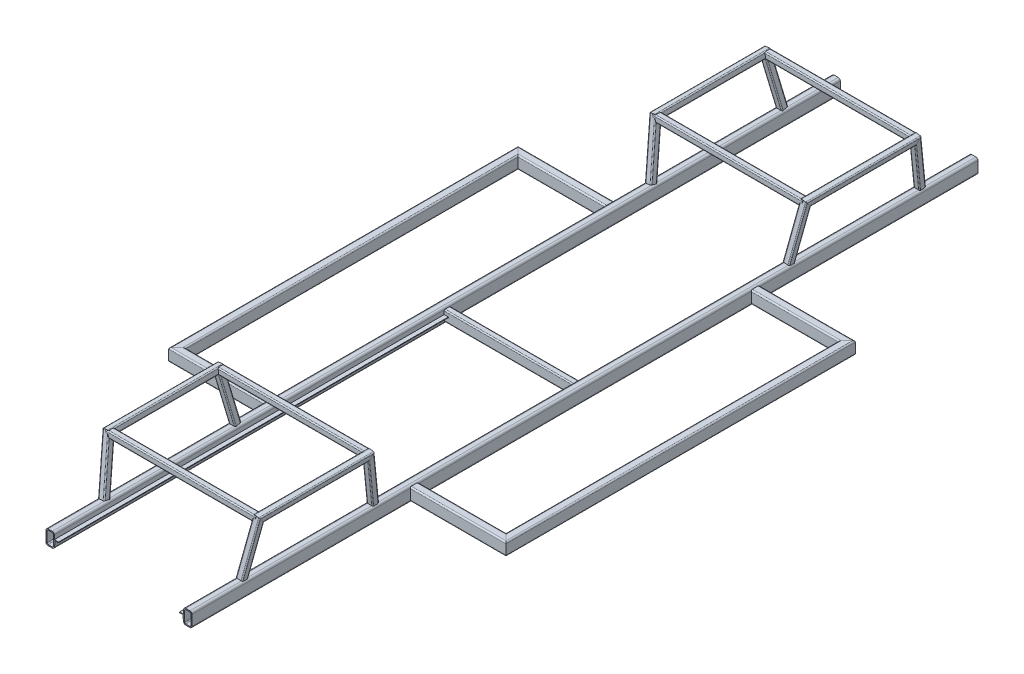
SolidWorks part; units mm, degrees
ref_plane "Płaszczyzna przednia" through (0, 0, 0) normal (0, 0, 1) x (1, 0, 0)
ref_plane "Płaszczyzna górna" through (0, 0, 0) normal (0, 1, 0) x (1, 0, 0)
ref_plane "Płaszczyzna prawa" through (0, 0, 0) normal (1, 0, 0) x (0, 0, -1)
sketch "Szkic1" plane through (0, 0, 0) normal (0, 1, 0) x (1, 0, 0)
  line L0 (-331, 3195) -> (-331, -585)
  line L1 (331, 3195) -> (331, -585)
  line L2 (0, 0) -> (0, -50000) construction
  line L3 (0, 0) -> (-50000, 0) construction
  line L4 (-331, 3195) -> (-50331, 3195) construction
  line L5 (-331, 1305) -> (331, 1305) construction
  line L6 (-331, 85) -> (331, 85) construction
  line L7 (-331, 2525) -> (331, 2525) construction
  line L8 (-331, 485) -> (-791, 485) construction
  line L9 (-791, 485) -> (-791, 2125) construction
  line L10 (-791, 2125) -> (-331, 2125) construction
  line L11 (331, 2125) -> (791, 2125) construction
  line L12 (791, 2125) -> (791, 485) construction
  line L13 (791, 485) -> (331, 485) construction
  dimension "D1" = 331
  dimension "D2" = 331
  dimension "D3" = 3780
  dimension "D4" = 3195
  dimension "D5" = 1220
  dimension "D6" = 1220
  dimension "D7" = 460
  dimension "D8" = 460
  dimension "D9" = 820
  dimension "D10" = 820
  dimension "D11" = 820
other "Rura prostokątna 70 X 40 X 5(1)"
ref_plane "Płaszczyzna1" through (-331, 0, -3195) normal (0, 0, 1) x (1, 0, 0)
sketch "Sketch11" plane through (-331, 0, -3195) normal (0, 0, 1) x (1, 0, 0)
  line L0 (-10, -30) -> (10, -30)
  line L1 (-15, -25) -> (-15, 25)
  line L2 (10, 30) -> (-10, 30)
  line L3 (15, 25) -> (15, -25)
  line L4 (-10, -35) -> (10, -35)
  line L5 (-20, -25) -> (-20, 25)
  line L6 (10, 35) -> (-10, 35)
  line L7 (20, 25) -> (20, -25)
  arc A0 (20, 25) -> (10, 35) centre (10, 25) ccw
  arc A1 (10, -35) -> (20, -25) centre (10, -25) ccw
  arc A2 (-20, -25) -> (-10, -35) centre (-10, -25) ccw
  arc A3 (-10, 35) -> (-20, 25) centre (-10, 25) ccw
  arc A4 (-10, 30) -> (-15, 25) centre (-10, 25) ccw
  arc A5 (15, 25) -> (10, 30) centre (10, 25) ccw
  arc A6 (10, -30) -> (15, -25) centre (10, -25) ccw
  arc A7 (-15, -25) -> (-10, -30) centre (-10, -25) ccw
  point P0 (0, 35)
  point P1 (20, 0)
  point P2 (0, -35)
  point P3 (-20, 0)
  point P4 (-20, 35)
  point P5 (20, 35)
  point P6 (20, -35)
  point P7 (-20, -35)
  point P8 (0, 0)
  point P33 (0, 0)
  dimension "D1" = 10
  dimension "Thickness" = 5
  dimension "V_leg" = 70
  dimension "H_leg" = 40
sketch "Szkic4" plane through (0, 0, 0) normal (0, 1, 0) x (1, 0, 0)
  line L0 (-331, 1305) -> (331, 1305)
  line L1 (-331, 3195) -> (-331, -585) construction
  line L2 (331, 3195) -> (331, -585) construction
other "Rura prostokątna 50 X 30 X 2.6(1)"
ref_plane "Płaszczyzna2" through (-331, 0, -1305) normal (1, 0, 0) x (0, 0, -1)
sketch "Sketch1" plane through (-331, 0, -1305) normal (1, 0, 0) x (0, 0, -1)
  line L0 (-9.8, -22.4) -> (9.8, -22.4)
  line L1 (-12.4, -19.8) -> (-12.4, 19.8)
  line L2 (9.8, 22.4) -> (-9.8, 22.4)
  line L3 (12.4, 19.8) -> (12.4, -19.8)
  line L4 (-9.8, -25) -> (9.8, -25)
  line L5 (-15, -19.8) -> (-15, 19.8)
  line L6 (9.8, 25) -> (-9.8, 25)
  line L7 (15, 19.8) -> (15, -19.8)
  arc A0 (15, 19.8) -> (9.8, 25) centre (9.8, 19.8) ccw
  arc A1 (9.8, -25) -> (15, -19.8) centre (9.8, -19.8) ccw
  arc A2 (-15, -19.8) -> (-9.8, -25) centre (-9.8, -19.8) ccw
  arc A3 (-9.8, 25) -> (-15, 19.8) centre (-9.8, 19.8) ccw
  arc A4 (-9.8, 22.4) -> (-12.4, 19.8) centre (-9.8, 19.8) ccw
  arc A5 (12.4, 19.8) -> (9.8, 22.4) centre (9.8, 19.8) ccw
  arc A6 (9.8, -22.4) -> (12.4, -19.8) centre (9.8, -19.8) ccw
  arc A7 (-12.4, -19.8) -> (-9.8, -22.4) centre (-9.8, -19.8) ccw
  point P0 (0, 25)
  point P1 (15, 0)
  point P2 (0, -25)
  point P3 (-15, 0)
  point P4 (-15, 25)
  point P5 (15, 25)
  point P6 (15, -25)
  point P7 (-15, -25)
  point P8 (0, 0)
  point P33 (0, 0)
  dimension "D1" = 5.2
  dimension "Thickness" = 2.6
  dimension "V_leg" = 50
  dimension "H_leg" = 30
sketch "Szkic6" plane through (0, 0, 0) normal (0, 1, 0) x (1, 0, 0)
  line L0 (-331, 2125) -> (-791, 2125)
  line L1 (-791, 2125) -> (-791, 485)
  line L2 (-791, 485) -> (-331, 485)
  line L3 (331, 2125) -> (791, 2125)
  line L4 (791, 2125) -> (791, 485)
  line L5 (791, 485) -> (331, 485)
other "Rura prostokątna 60 X 40 X 3.2(1)"
ref_plane "Płaszczyzna3" through (-791, 0, -485) normal (1, 0, 0) x (0, 0, -1)
sketch "Sketch12" plane through (-791, 0, -485) normal (1, 0, 0) x (0, 0, -1)
  line L0 (-13.6, -26.8) -> (13.6, -26.8)
  line L1 (-16.8, -23.6) -> (-16.8, 23.6)
  line L2 (13.6, 26.8) -> (-13.6, 26.8)
  line L3 (16.8, 23.6) -> (16.8, -23.6)
  line L4 (-13.6, -30) -> (13.6, -30)
  line L5 (-20, -23.6) -> (-20, 23.6)
  line L6 (13.6, 30) -> (-13.6, 30)
  line L7 (20, 23.6) -> (20, -23.6)
  arc A0 (20, 23.6) -> (13.6, 30) centre (13.6, 23.6) ccw
  arc A1 (13.6, -30) -> (20, -23.6) centre (13.6, -23.6) ccw
  arc A2 (-20, -23.6) -> (-13.6, -30) centre (-13.6, -23.6) ccw
  arc A3 (-13.6, 30) -> (-20, 23.6) centre (-13.6, 23.6) ccw
  arc A4 (-13.6, 26.8) -> (-16.8, 23.6) centre (-13.6, 23.6) ccw
  arc A5 (16.8, 23.6) -> (13.6, 26.8) centre (13.6, 23.6) ccw
  arc A6 (13.6, -26.8) -> (16.8, -23.6) centre (13.6, -23.6) ccw
  arc A7 (-16.8, -23.6) -> (-13.6, -26.8) centre (-13.6, -23.6) ccw
  point P0 (0, 30)
  point P1 (20, 0)
  point P2 (0, -30)
  point P3 (-20, 0)
  point P4 (-20, 30)
  point P5 (20, 30)
  point P6 (20, -30)
  point P7 (-20, -30)
  point P8 (0, 0)
  point P33 (0, 0)
  dimension "D1" = 6.4
  dimension "Thickness" = 3.2
  dimension "V_leg" = 60
  dimension "H_leg" = 40
ref_plane "Płaszczyzna4" through (-331, 0, 0) normal (-1, 0, 0) x (0, 0, 1)
sketch "Szkic8" plane through (-331, 0, 0) normal (-1, 0, 0) x (0, 0, 1)
  line L0 (-2125, 0) -> (-2125, 95)
  line L1 (-2125, 0) -> (-485, 0) construction
  line L2 (-2125, 0) -> (-485, 0) construction
  line L4 (-3195, 0) -> (-3195, 50000) construction
  line L5 (-3195, 25) -> (-3195, -25) construction
  point P15 (-3195, 0)
  dimension "D1" = 95
  dimension "D2" = 1070
sketch "Szkic9" plane through (-331, 0, 0) normal (-1, 0, 0) x (0, 0, 1)
  line L0 (-2125, 0) -> (-2305, 0)
  line L1 (-200000, 0) -> (250000, 0) construction
  line L2 (-2305, 0) -> (-2305, 35)
  line L3 (585, 35) -> (-3195, 35) construction
  line L4 (-2305, 35) -> (-2935, 35)
  dimension "D1" = 180
  dimension "D2" = 630
sketch "Szkic10" plane through (-331, 0, 0) normal (-1, 0, 0) x (0, 0, 1)
  line L0 (-2305, 35) -> (-2305, 275) construction
  line L1 (-2305, 35) -> (-2356.0136, 275) construction
  line L2 (-2935, 35) -> (-2935, 275) construction
  line L3 (-2935, 35) -> (-2883.9864, 275) construction
  line L4 (-2935, 155) -> (-2911, 155) construction
  dimension "D1" = 240
  dimension "D2" = 12
  dimension "D3" = 12
  dimension "D4" = 120
  dimension "D5" = 24
sketch "Szkic11" plane through (0, 35, 0) normal (0, 1, 0) x (1, 0, 0)
  line L0 (-331, 2305) -> (331, 2305) construction
  line L1 (-331, 2305) -> (-331, 2935) construction
  line L2 (-331, 2125) -> (-331, 2305) construction
  line L3 (-331, 2935) -> (331, 2935) construction
  line L4 (351, -585) -> (351, 3195) construction
  dimension "D1" = 20
  dimension "D2" = 20
ref_plane "Płaszczyzna5" through (0, 598.399, -2815.2459) normal (0, -0.2079, 0.9781) x (1, 0, 0)
ref_plane "Płaszczyzna6" through (0, -467.251, -2198.2432) normal (0, 0.2079, 0.9781) x (1, 0, 0)
sketch "Szkic12" plane through (0, 598.399, -2815.2459) normal (0, -0.2079, 0.9781) x (1, 0, 0)
  line L0 (-331, -575.9856) -> (-331, -330.6239) construction
  line L1 (-331, -575.9856) -> (-331, -341.2302) construction
  line L2 (0, -55) -> (0, 55) construction
  line L3 (331, -575.9856) -> (331, -330.6239) construction
  line L4 (-331, -575.9856) -> (-361, -330.6239)
  line L5 (331, -575.9856) -> (361, -330.6239)
  line L6 (361, -330.6239) -> (-361, -330.6239) construction
  dimension "D1" = 30
  dimension "D2" = 30
sketch "Szkic13" plane through (0, -467.251, -2198.2432) normal (0, 0.2079, 0.9781) x (1, 0, 0)
  line L0 (-331, 513.4716) -> (-331, 758.8334) construction
  line L1 (-331, 513.4716) -> (-331, 758.8334) construction
  line L2 (-331, 513.4716) -> (-331, 748.227) construction
  line L3 (0, -55) -> (0, 55) construction
  line L4 (331, 513.4716) -> (331, 758.8334) construction
  line L5 (-331, 513.4716) -> (-361, 758.8334)
  line L6 (-361, 758.8334) -> (361, 758.8334) construction
  arc A0 (331, 513.4716) -> (361, 758.8334) centre (1349.3731, 513.4716) cw
  dimension "D1" = 30
  dimension "D2" = 30
ref_plane "Płaszczyzna7" through (-321.6, -40.2, 0) normal (-0.9923, -0.124, 0) x (0, 0, 1)
sketch "Szkic14" plane through (-321.6, -40.2, 0) normal (-0.9923, -0.124, 0) x (0, 0, 1)
  line L0 (-2935, 75.7852) -> (-2883.9864, 317.653)
  line L3 (-2883.9864, 317.653) -> (-2356.0136, 317.653)
  line L5 (-2356.0136, 317.653) -> (-2305, 75.7852)
other "Rura kwadratowa 30 X 30 X 2.6(2)"
ref_plane "Płaszczyzna9" through (-331, 35, -2935) normal (-0.1214, 0.9709, 0.2064) x (-0.0256, 0.2048, -0.9785)
sketch "Sketch14" plane through (-331, 35, -2935) normal (-0.1214, 0.9709, 0.2064) x (-0.0256, 0.2048, -0.9785)
  line L0 (-9.8, -12.4) -> (9.8, -12.4)
  line L1 (-12.4, -9.8) -> (-12.4, 9.8)
  line L2 (9.8, 12.4) -> (-9.8, 12.4)
  line L3 (12.4, 9.8) -> (12.4, -9.8)
  line L4 (-9.8, -15) -> (9.8, -15)
  line L5 (-15, -9.8) -> (-15, 9.8)
  line L6 (9.8, 15) -> (-9.8, 15)
  line L7 (15, 9.8) -> (15, -9.8)
  arc A0 (15, 9.8) -> (9.8, 15) centre (9.8, 9.8) ccw
  arc A1 (9.8, -15) -> (15, -9.8) centre (9.8, -9.8) ccw
  arc A2 (-15, -9.8) -> (-9.8, -15) centre (-9.8, -9.8) ccw
  arc A3 (-9.8, 15) -> (-15, 9.8) centre (-9.8, 9.8) ccw
  arc A4 (-9.8, 12.4) -> (-12.4, 9.8) centre (-9.8, 9.8) ccw
  arc A5 (12.4, 9.8) -> (9.8, 12.4) centre (9.8, 9.8) ccw
  arc A6 (9.8, -12.4) -> (12.4, -9.8) centre (9.8, -9.8) ccw
  arc A7 (-12.4, -9.8) -> (-9.8, -12.4) centre (-9.8, -9.8) ccw
  point P0 (-15, 0)
  point P1 (15, 0)
  point P2 (0, 15)
  point P3 (0, -15)
  point P4 (0, 0)
  point P5 (-15, -15)
  point P6 (15, -15)
  point P7 (15, 15)
  point P8 (-15, 15)
  point P33 (0, 0)
  dimension "D1" = 5.2
  dimension "Thickness" = 2.6
  dimension "V_leg" = 30
mirror "Lustro1" about plane through (0, 0, 0) normal (1, 0, 0) of bodies 113 114 115
ref_plane "Płaszczyzna10" through (0, 275, 0) normal (0, 1, 0) x (1, 0, 0)
sketch "Szkic17" plane through (0, 275, 0) normal (0, 1, 0) x (1, 0, 0)
  line L0 (361, 2356.0136) -> (-361, 2356.0136)
  line L1 (361, 2883.9864) -> (-361, 2883.9864)
  line L2 (-361, 2356.0136) -> (361, 2356.0136) construction
  line L3 (361, 2883.9864) -> (-361, 2883.9864) construction
other "Rura kwadratowa 30 X 30 X 2.6(3)"
ref_plane "Płaszczyzna11" through (361, 275, -2356.0136) normal (-1, 0, 0) x (0, 0, 1)
sketch "Sketch15" plane through (361, 275, -2356.0136) normal (-1, 0, 0) x (0, 0, 1)
  line L0 (-9.8, -12.4) -> (9.8, -12.4)
  line L1 (-12.4, -9.8) -> (-12.4, 9.8)
  line L2 (9.8, 12.4) -> (-9.8, 12.4)
  line L3 (12.4, 9.8) -> (12.4, -9.8)
  line L4 (-9.8, -15) -> (9.8, -15)
  line L5 (-15, -9.8) -> (-15, 9.8)
  line L6 (9.8, 15) -> (-9.8, 15)
  line L7 (15, 9.8) -> (15, -9.8)
  arc A0 (15, 9.8) -> (9.8, 15) centre (9.8, 9.8) ccw
  arc A1 (9.8, -15) -> (15, -9.8) centre (9.8, -9.8) ccw
  arc A2 (-15, -9.8) -> (-9.8, -15) centre (-9.8, -9.8) ccw
  arc A3 (-9.8, 15) -> (-15, 9.8) centre (-9.8, 9.8) ccw
  arc A4 (-9.8, 12.4) -> (-12.4, 9.8) centre (-9.8, 9.8) ccw
  arc A5 (12.4, 9.8) -> (9.8, 12.4) centre (9.8, 9.8) ccw
  arc A6 (9.8, -12.4) -> (12.4, -9.8) centre (9.8, -9.8) ccw
  arc A7 (-12.4, -9.8) -> (-9.8, -12.4) centre (-9.8, -9.8) ccw
  point P0 (-15, 0)
  point P1 (15, 0)
  point P2 (0, 15)
  point P3 (0, -15)
  point P4 (0, 0)
  point P5 (-15, -15)
  point P6 (15, -15)
  point P7 (15, 15)
  point P8 (-15, 15)
  point P33 (0, 0)
  dimension "D1" = 5.2
  dimension "Thickness" = 2.6
  dimension "V_leg" = 30
ref_plane "Płaszczyzna12" through (0, 0, -1305) normal (0, 0, -1) x (-1, 0, 0)
mirror "Lustro2" about plane through (0, 0, -1305) normal (0, 0, -1) of bodies 113 114 115 118 117 116 120 119
sketch "Szkic19" plane through (0, 0, 585) normal (0, 0, -1) x (-1, 0, 0)
  line L0 (-311, 5) -> (-311, -15)
  line L1 (-311, 25) -> (-311, -25) construction
  line L2 (-311, -15) -> (-308, -15)
  line L3 (-308, -15) -> (-308, -1.5)
  line L4 (-304.5, 2) -> (-291, 2)
  line L5 (-291, 2) -> (-291, 5)
  line L6 (-291, 5) -> (-311, 5)
  line L7 (-341, 35) -> (-321, 35) construction
  arc A0 (-308, -1.5) -> (-304.5, 2) centre (-304.5, -1.5) cw
  dimension "D6" = 3.5
  dimension "D1" = 30
  dimension "D2" = 20
  dimension "D3" = 20
  dimension "D4" = 3
  dimension "D5" = 3
extrude "Dodanie-wyciągnięcie1" add sketch "Szkic19" along normal up to surface (1875 mm away) separate body up to face at (0, 0, -1290)
mirror "Lustro3" about plane through (0, 0, 0) normal (1, 0, 0) of bodies 129
